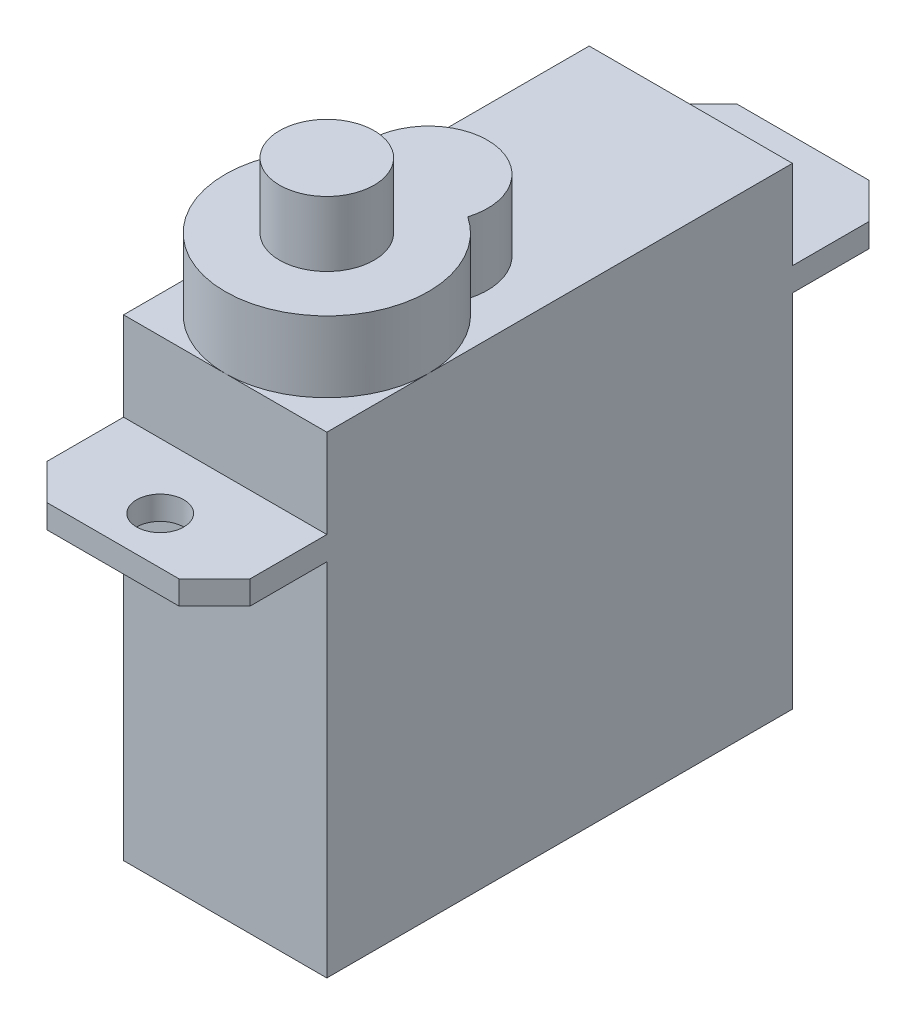
SolidWorks part; units mm, degrees
ref_plane "前视基准面" through (0, 0, 0) normal (0, 0, 1) x (1, 0, 0)
ref_plane "上视基准面" through (0, 0, 0) normal (0, 1, 0) x (1, 0, 0)
ref_plane "右视基准面" through (0, 0, 0) normal (1, 0, 0) x (0, 0, -1)
sketch "Sketch1" plane through (0, 0, 0) normal (1, 0, 0) x (0, 0, -1)
  line L0 (9.85, -3.75) -> (14.6, -3.75)
  line L1 (-9.85, 0) -> (9.85, 0)
  line L2 (-9.85, 0) -> (-9.85, -3.75)
  line L3 (-9.85, -20) -> (9.85, -20)
  line L4 (9.85, 0) -> (9.85, -3.75)
  line L5 (-14.6, -3.75) -> (-9.85, -3.75)
  line L6 (-14.6, -3.75) -> (-14.6, -4.75)
  line L7 (-14.6, -4.75) -> (-9.85, -4.75)
  line L8 (14.6, -3.75) -> (14.6, -4.75)
  line L9 (9.85, -4.75) -> (14.6, -4.75)
  line L10 (-9.85, -4.75) -> (-9.85, -20)
  line L11 (9.85, -4.75) -> (9.85, -20)
  dimension "D1" = 19.7
  dimension "D2" = 20
  dimension "D3" = 3.75
  dimension "D4" = 4.75
  dimension "D5" = 1
extrude "Boss-Extrude1" add sketch "Sketch1" along normal blind 8.6
sketch "Sketch2" plane through (0, 0, 0) normal (0, 1, 0) x (1, 0, 0)
  line L0 (8.6, -9.85) -> (0, -9.85) construction
  line L3 (8.6, 9.85) -> (8.6, -9.85) construction
  line L4 (0, 9.85) -> (0, -9.85) construction
  arc A0 (1.908, -1.9767) -> (6.692, -1.9767) centre (4.3, -5.55) ccw
  arc A1 (6.692, -1.9767) -> (1.908, -1.9767) centre (4.3, -1.25) ccw
  dimension "D1" = 5
extrude "Boss-Extrude2" add sketch "Sketch2" along normal blind 3
sketch "Sketch3" plane through (0, 3, 0) normal (0, 1, 0) x (1, 0, 0)
  circle A0 centre (4.3, -5.55) radius 2
  dimension "D1" = 4
extrude "Boss-Extrude3" add sketch "Sketch3" along normal blind 2.75
sketch "Sketch4" plane through (0, -3.75, 0) normal (0, 1, 0) x (1, 0, 0)
  line L0 (4.3, -12.6) -> (4.3, -14.6) construction
  line L2 (8.6, -14.6) -> (0, -14.6) construction
  circle A0 centre (4.3, -12.6) radius 1
  dimension "D1" = 2
  dimension "D2" = 2
extrude "Cut-Extrude1" cut sketch "Sketch4" against normal up to next
mirror "Mirror1" about plane through (0, 0, 0) normal (0, 0, 1) of "Cut-Extrude1"
chamfer "Chamfer1" distance 1.5 angle 45 4 edges at (0, -4.25, -14.6) (8.6, -4.25, -14.6) (8.6, -4.25, 14.6) (0, -4.25, 14.6)
